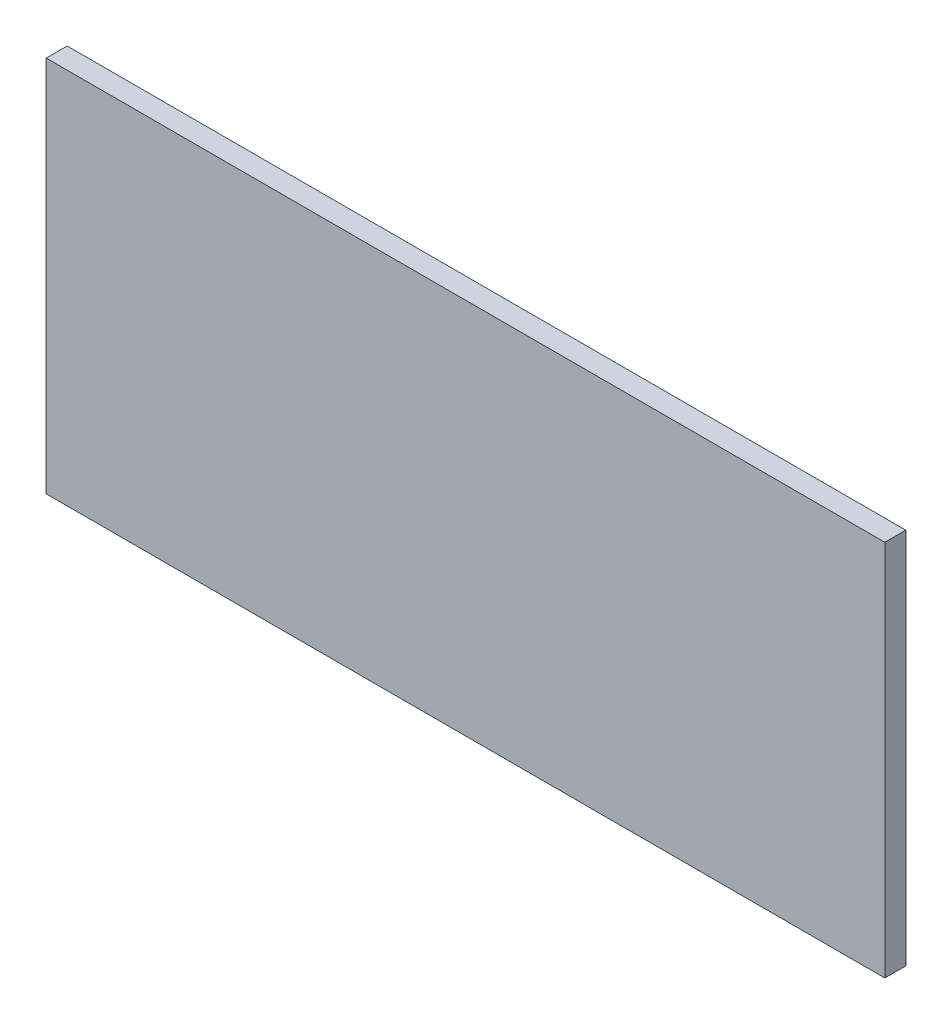
SolidWorks part; units mm, degrees
material "Balsa"
ref_plane "Plan de face" through (0, 0, 0) normal (0, 0, 1) x (1, 0, 0)
ref_plane "Plan de dessus" through (0, 0, 0) normal (0, 1, 0) x (1, 0, 0)
ref_plane "Plan de droite" through (0, 0, 0) normal (1, 0, 0) x (0, 0, -1)
sketch "Esquisse1" plane through (0, 0, 0) normal (0, 0, 1) x (1, 0, 0)
  line L1 (0, 0) -> (-400, 0)
  line L2 (0, 0) -> (0, 180)
  line L3 (0, 180) -> (-400, 180)
  line L4 (-400, 0) -> (-400, 180)
  dimension "D1" = 400
  dimension "D2" = 180
extrude "Boss.-Extru.1" add sketch "Esquisse1" along normal blind 10
